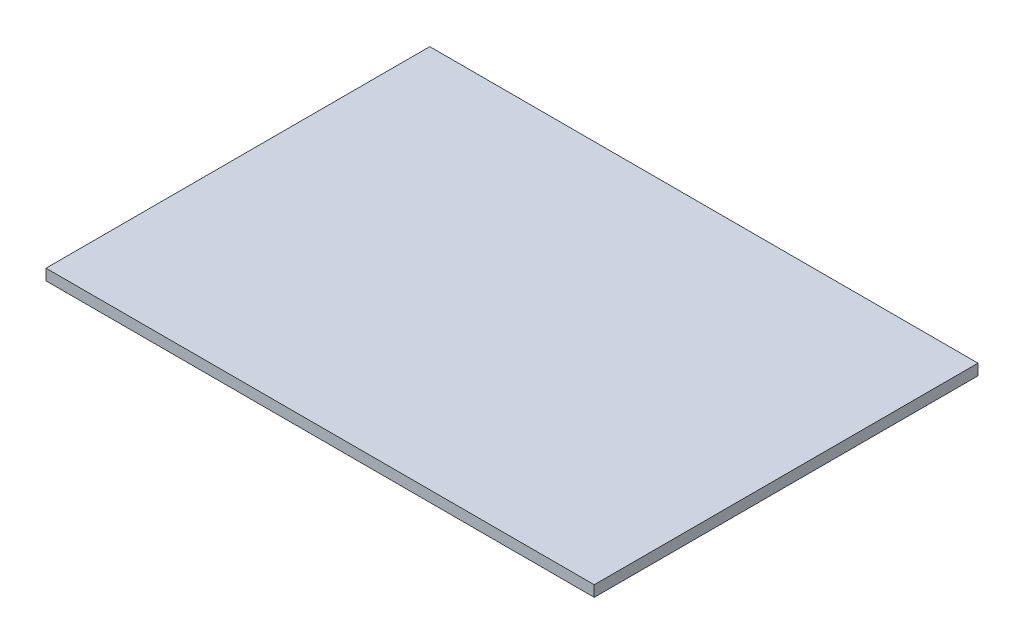
SolidWorks part; units mm, degrees
ref_plane "Front Plane" through (0, 0, 0) normal (0, 0, 1) x (1, 0, 0)
ref_plane "Top Plane" through (0, 0, 0) normal (0, 1, 0) x (1, 0, 0)
ref_plane "Right Plane" through (0, 0, 0) normal (1, 0, 0) x (0, 0, -1)
sketch "Sketch1" plane through (0, 0, 0) normal (0, 1, 0) x (1, 0, 0)
  line L1 (250, -175) -> (-250, -175)
  line L2 (250, -175) -> (250, 175)
  line L3 (250, 175) -> (-250, 175)
  line L4 (-250, -175) -> (-250, 175)
  line L5 (250, -175) -> (-250, 175) construction
  line L6 (250, 175) -> (-250, -175) construction
  point P0 (0, 0)
  dimension "D1" = 350
  dimension "D2" = 500
extrude "Boss-Extrude1" add sketch "Sketch1" along normal blind 10
